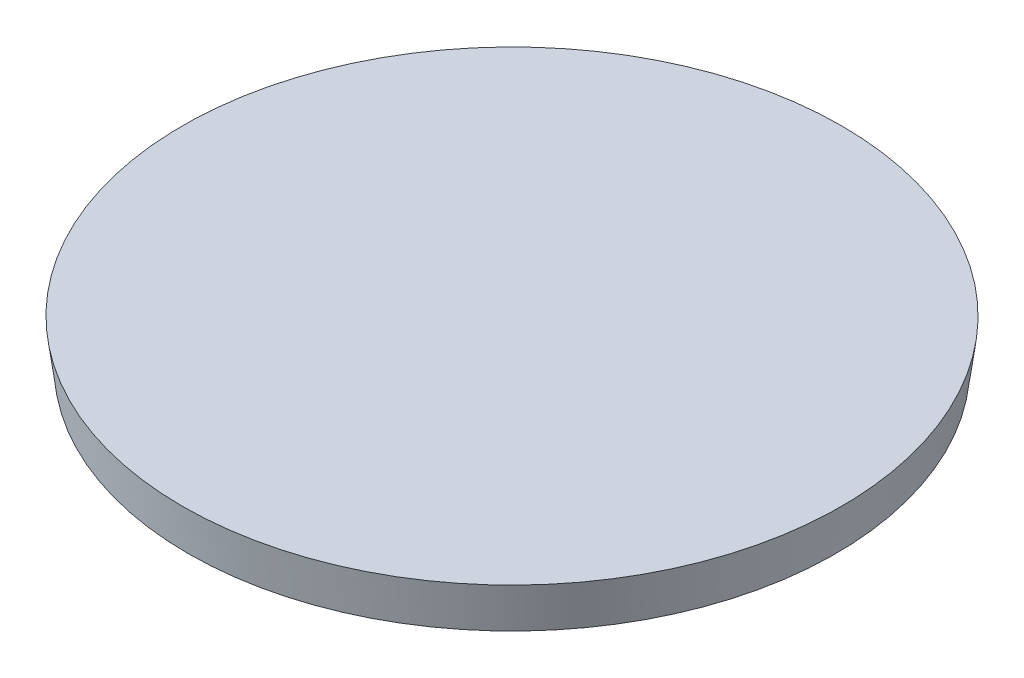
SolidWorks part; units mm, degrees
material "Brass"
ref_plane "Front Plane" through (0, 0, 0) normal (0, 0, 1) x (1, 0, 0)
ref_plane "Top Plane" through (0, 0, 0) normal (0, 1, 0) x (1, 0, 0)
ref_plane "Right Plane" through (0, 0, 0) normal (1, 0, 0) x (0, 0, -1)
sketch "Sketch2" plane through (0, 0, 0) normal (0, 0, 1) x (1, 0, 0)
  line L0 (0, 0) -> (11.2395, 0)
  line L1 (11.2395, 0) -> (11.4401, 1.524)
  line L2 (11.4401, 1.524) -> (0, 1.524)
  line L4 (0, 1.524) -> (0, 0) construction
  line L5 (0, 1.524) -> (0, 0)
  dimension "D1" = 1.524
  dimension "D2" = 22.479
  dimension "D3" = 7.5
revolve "Revolve1" add sketch "Sketch2" angle 360 about L4
